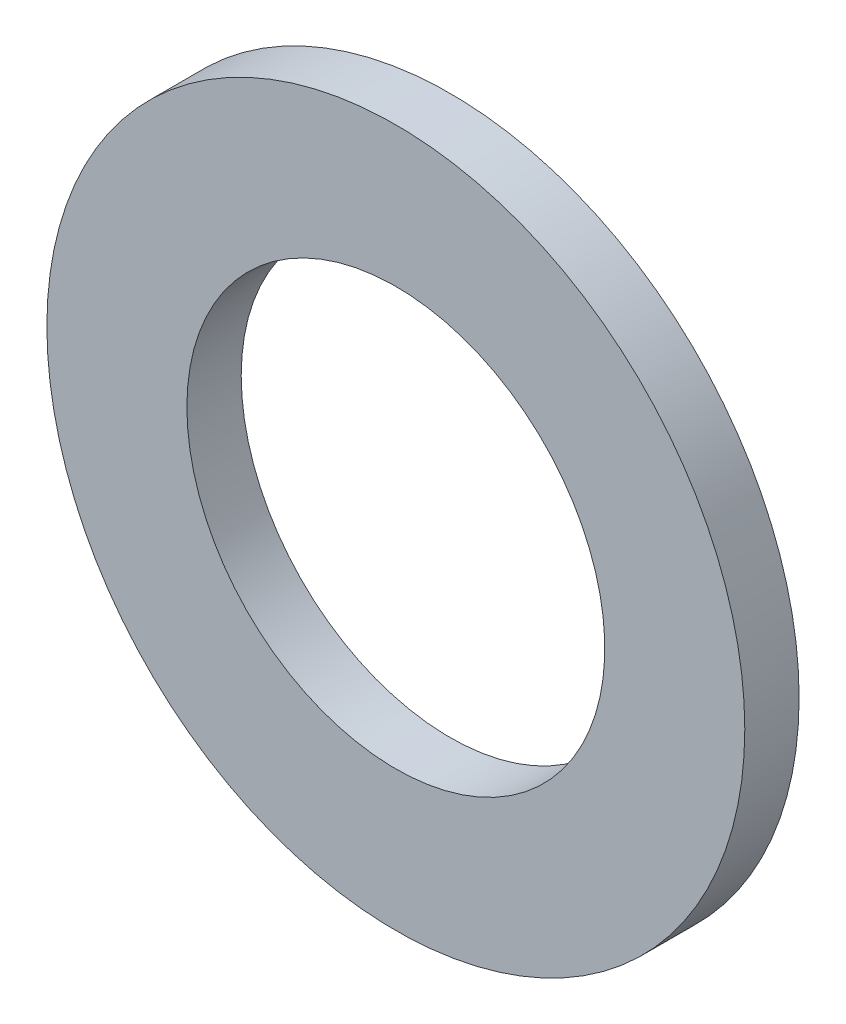
SolidWorks part; units mm, degrees
material "Plain Carbon Steel"
ref_plane "Front Plane" through (0, 0, 0) normal (0, 0, 1) x (1, 0, 0)
ref_plane "Top Plane" through (0, 0, 0) normal (0, 1, 0) x (1, 0, 0)
ref_plane "Right Plane" through (0, 0, 0) normal (1, 0, 0) x (0, 0, -1)
sketch "Sketch1" plane through (0, 0, 0) normal (0, 0, 1) x (1, 0, 0)
  circle A0 centre (0, 0) radius 12.7
  circle A1 centre (0, 0) radius 21.209
  dimension "D1" = 42.418
  dimension "D2" = 25.4
extrude "Boss-Extrude1" add sketch "Sketch1" along normal blind 3.302
